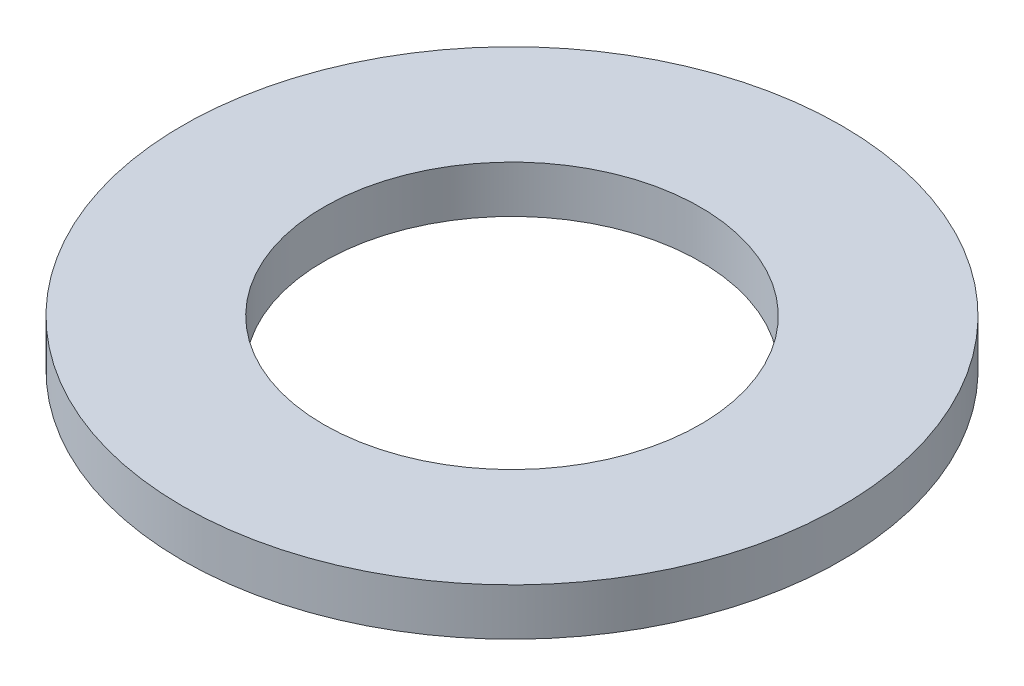
SolidWorks part; units mm, degrees
material "Commercially Pure CP-Ti UNS R50700  Grade 4 (SS)"
ref_plane "Front Plane" through (0, 0, 0) normal (0, 0, 1) x (1, 0, 0)
ref_plane "Top Plane" through (0, 0, 0) normal (0, 1, 0) x (1, 0, 0)
ref_plane "Right Plane" through (0, 0, 0) normal (1, 0, 0) x (0, 0, -1)
other "Bounding Box"
ref_plane "Default Plane" through (-8.9266, -12.7485, 0) normal (-0.1736, 0.9848, 0) x (0.9848, 0.1736, 0)
sketch "Sketch1" plane through (0, 0, 0) normal (0, 1, 0) x (1, 0, 0)
  circle A0 centre (0, 0) radius 6.35
  circle A1 centre (0, 0) radius 11.1125
  dimension "D1" = 12.7
  dimension "D2" = 22.225
extrude "Boss-Extrude1" add sketch "Sketch1" along normal mid plane 1.5875
